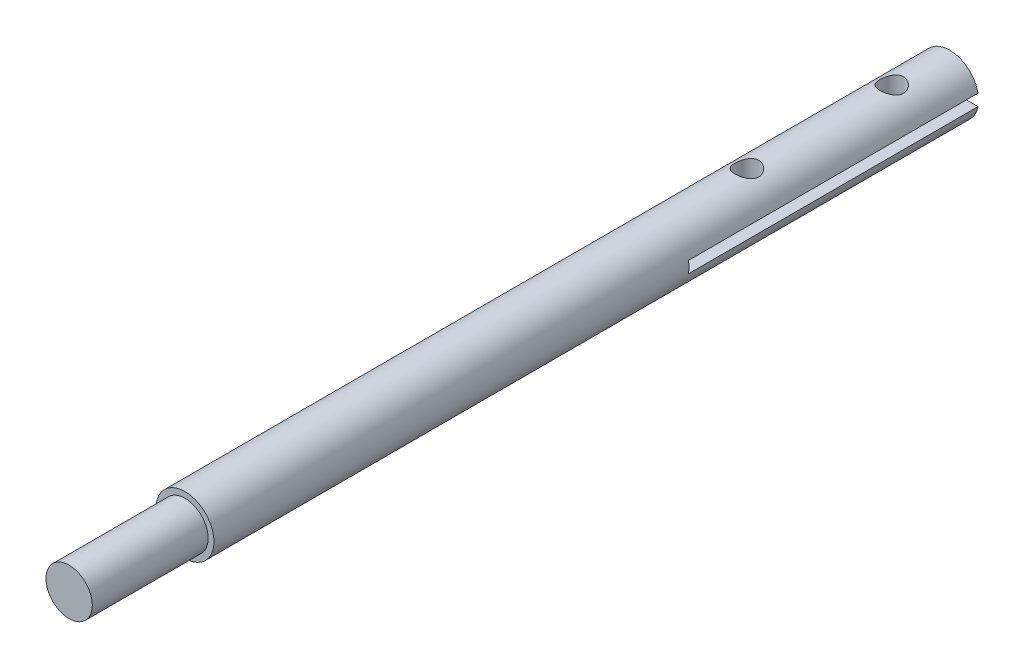
SolidWorks part; units mm, degrees
material "1060 Alloy"
ref_plane "Front" through (0, 0, 0) normal (0, 0, 1) x (1, 0, 0)
ref_plane "Top" through (0, 0, 0) normal (0, 1, 0) x (1, 0, 0)
ref_plane "Right" through (0, 0, 0) normal (1, 0, 0) x (0, 0, -1)
sketch "Sketch1" plane through (0, 0, 0) normal (0, 0, 1) x (1, 0, 0)
  circle A0 centre (0, 0) radius 5
  dimension "D1" = 10
extrude "Boss-Extrude1" add sketch "Sketch1" along normal blind 152
sketch "Sketch2" plane through (0, 0, 152) normal (0, 0, 1) x (1, 0, 0)
  line L1 (-7.5, 2.5) -> (7.5, 2.5)
  line L2 (-7.5, 2.5) -> (-7.5, -2.5)
  line L3 (-7.5, -2.5) -> (7.5, -2.5)
  line L4 (7.5, 2.5) -> (7.5, -2.5)
  point P4 (-7.5, 0)
  point P5 (0, 2.5)
  dimension "D1" = 5
  dimension "D2" = 15
sketch "Sketch3" plane through (0, 0, 0) normal (0, 1, 0) x (1, 0, 0)
  line L1 (5, 0) -> (-5, 0) construction
  circle A0 centre (0, -10) radius 2.05
  circle A1 centre (0, -35) radius 2.05
  dimension "D1" = 4.1
  dimension "D2" = 4.1
  dimension "D3" = 25
  dimension "D4" = 10
extrude "Cut-Extrude2" cut sketch "Sketch3" against normal through all and the other way through all
sketch "Sketch5" plane through (0, 0, 0) normal (0, 0, -1) x (-1, 0, 0)
  line L1 (-7.5, 1) -> (7.5, 1)
  line L2 (-7.5, 1) -> (-7.5, -1)
  line L3 (-7.5, -1) -> (7.5, -1)
  line L4 (7.5, 1) -> (7.5, -1)
  point P4 (0, 1)
  point P5 (-7.5, 0)
  dimension "D1" = 15
  dimension "D2" = 2
extrude "Cut-Extrude4" cut sketch "Sketch5" against normal blind 50
sketch "Sketch6" plane through (0, 0, 152) normal (0, 0, 1) x (1, 0, 0)
  circle A0 centre (0, 0) radius 4
  dimension "D1" = 8
extrude "Cut-Extrude5" cut sketch "Sketch6" against normal blind 20 flip side to cut
